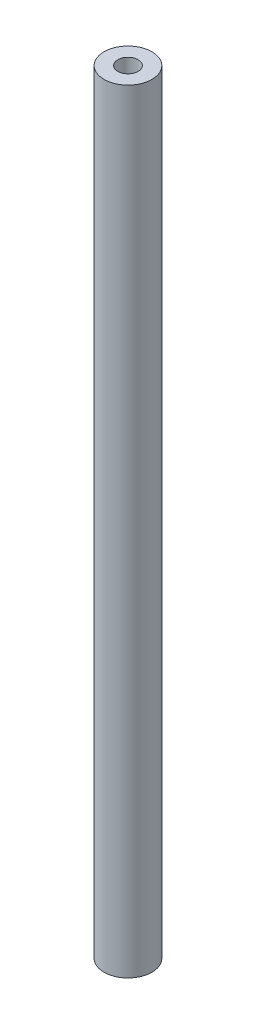
SolidWorks part; units mm, degrees
material "6061-T6 (SS)"
ref_plane "Front Plane" through (0, 0, 0) normal (0, 0, 1) x (1, 0, 0)
ref_plane "Top Plane" through (0, 0, 0) normal (0, 1, 0) x (1, 0, 0)
ref_plane "Right Plane" through (0, 0, 0) normal (1, 0, 0) x (0, 0, -1)
sketch "Sketch1" plane through (0, 0, 0) normal (0, 1, 0) x (1, 0, 0)
  circle A0 centre (0, 0) radius 4.7625
  dimension "D1" = 9.525
extrude "Boss-Extrude1" add sketch "Sketch1" along normal blind 153.7335
hole_wizard "#10-32 Tapped Hole1" positions "Sketch2" profile "Sketch3" tap size "#10-32" standard "ANSI Inch"
sketch "Sketch2" plane through (0, 0, 0) normal (0, -1, 0) x (-1, 0, 0)
  point P0 (0, 0)
sketch "Sketch3" plane through (0, 0, 0) normal (1, 0, 0) x (0, 0, -1)
  line L0 (0, 0) -> (0, 11.3733)
  line L1 (0, 11.3733) -> (2.0193, 10.16)
  line L2 (2.0193, 10.16) -> (2.0193, 0)
  line L5 (2.0193, 0) -> (0, 0)
  line L10 (0, 11.3733) -> (-2.0193, 10.16) construction
  line L11 (0, -6.35) -> (0, 107.95) construction
  dimension "Tap Drill Dia." = 4.0386
  dimension "Tap Drill Depth" = 10.16
  dimension "Drill Angle" = 118
cosmetic thread "Hole Thread1"
hole_wizard "#10-32 Tapped Hole2" positions "Sketch4" profile "Sketch5" tap size "#10-32" standard "ANSI Inch"
sketch "Sketch4" plane through (0, 153.7335, 0) normal (0, 1, 0) x (1, 0, 0)
  point P0 (0, 0)
sketch "Sketch5" plane through (0, 153.7335, 0) normal (1, 0, 0) x (0, 0, 1)
  line L0 (0, 0) -> (0, 13.1513)
  line L1 (0, 13.1513) -> (2.0193, 11.938)
  line L2 (2.0193, 11.938) -> (2.0193, 0)
  line L5 (2.0193, 0) -> (0, 0)
  line L10 (0, 13.1513) -> (-2.0193, 11.938) construction
  line L11 (0, -6.35) -> (0, 107.95) construction
  dimension "Tap Drill Dia." = 4.0386
  dimension "Tap Drill Depth" = 11.938
  dimension "Drill Angle" = 118
cosmetic thread "Hole Thread2"
